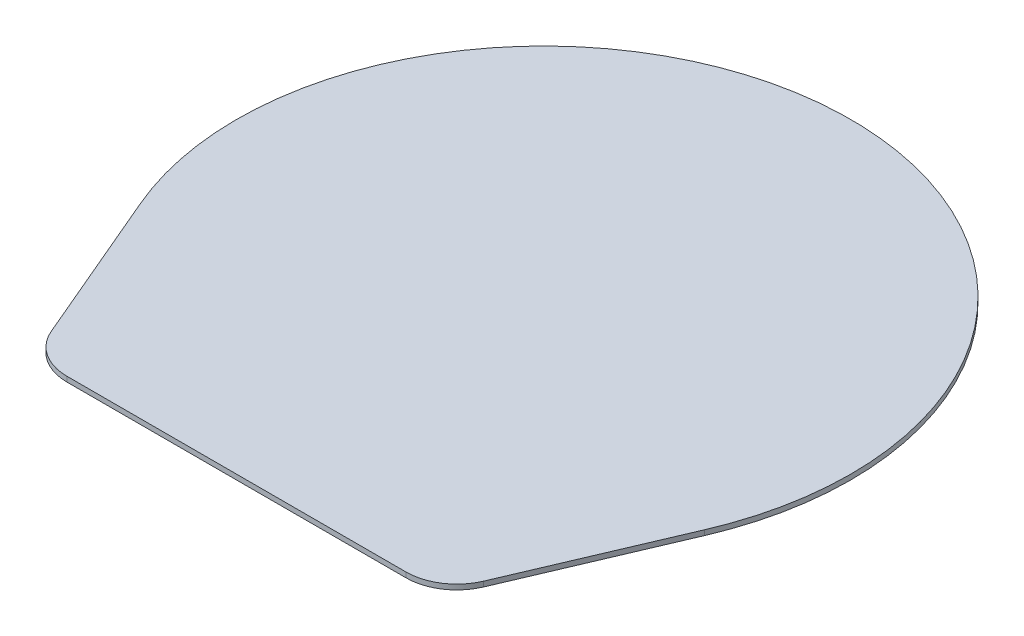
SolidWorks part; units mm, degrees
ref_plane "Front Plane" through (0, 0, 0) normal (0, 0, 1) x (1, 0, 0)
ref_plane "Top Plane" through (0, 0, 0) normal (0, 1, 0) x (1, 0, 0)
ref_plane "Right Plane" through (0, 0, 0) normal (1, 0, 0) x (0, 0, -1)
sketch "Sketch1" plane through (0, 0, 0) normal (0, 1, 0) x (1, 0, 0)
  circle A0 centre (0, 0) radius 60.5
  dimension "D1" = 121
extrude "Boss-Extrude1" add sketch "Sketch1" along normal blind 1
sketch "Sketch7" plane through (0, 1, 0) normal (0, 1, 0) x (1, 0, 0)
  line L0 (0, 0) -> (0, -65.9406) construction
  line L1 (-40, -60.5) -> (40, -60.5)
  line L2 (55.7555, -23.4856) -> (40, -60.5)
  line L3 (-55.7555, -23.4856) -> (-40, -60.5)
  circle A0 centre (0, 0) radius 60.5 construction
  circle A1 centre (0, 0) radius 60.5
  point P10 (0, -60.5)
  dimension "D1" = 40
extrude "Boss-Extrude2" add sketch "Sketch7" against normal blind 1 contours A1 L3 L1 | A1 L1 L2
fillet "Fillet1" radius 10 2 edges at (40, 0.5, 60.5) (-40, 0.5, 60.5)
